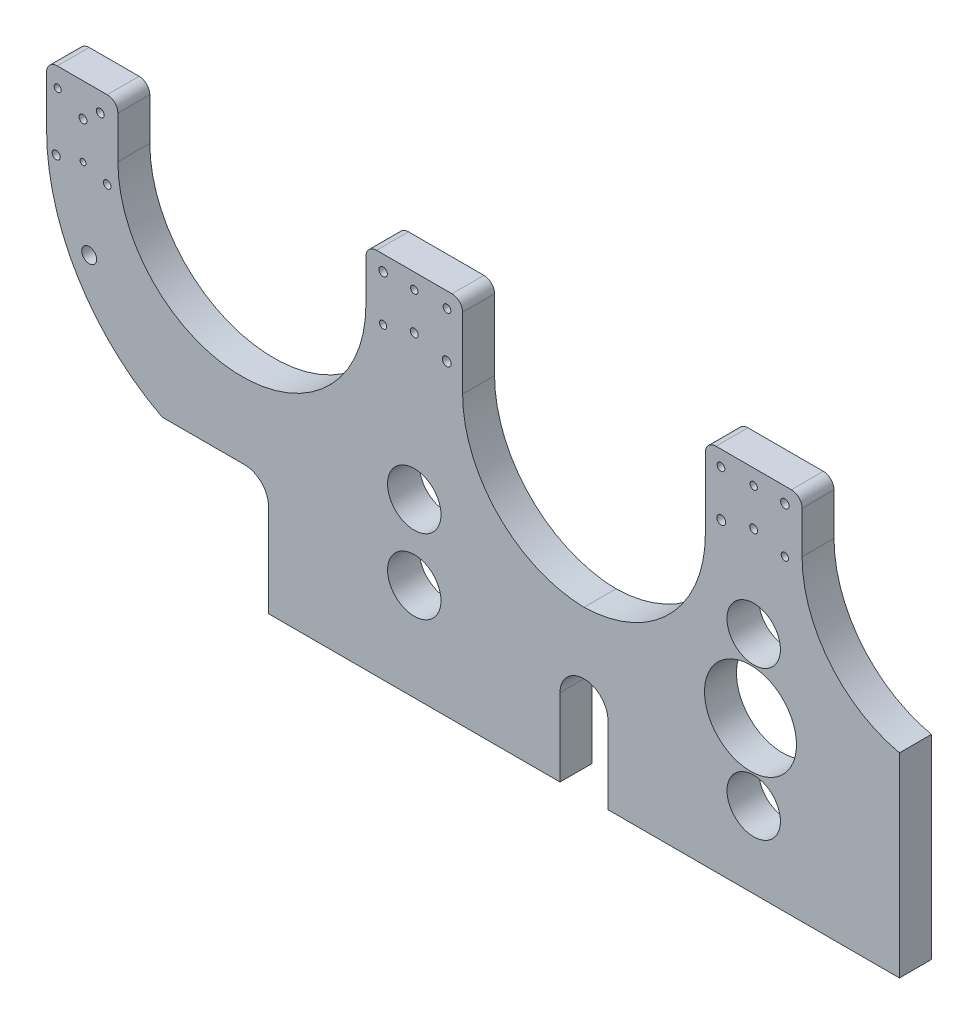
SolidWorks part; units mm, degrees
ref_plane "Front Plane" through (0, 0, 0) normal (0, 0, 1) x (1, 0, 0)
ref_plane "Top Plane" through (0, 0, 0) normal (0, 1, 0) x (1, 0, 0)
ref_plane "Right Plane" through (0, 0, 0) normal (1, 0, 0) x (0, 0, -1)
sketch "Sketch1" plane through (0, 0, 0) normal (0, 0, 1) x (1, 0, 0)
  line L0 (-439.926, 0) -> (394.926, 0) construction
  line L1 (0, 0) -> (0, 298.5319) construction
  line L2 (0, 0) -> (296.37, 0)
  line L3 (296.37, 0) -> (296.37, 183.19)
  line L4 (204.87, 336.4641) -> (204.87, 296.976)
  line L5 (194.87, 346.4641) -> (124, 346.4641)
  line L6 (114, 336.4641) -> (114, 269.898)
  line L7 (22.5, 0) -> (22.5, 72.7462)
  line L8 (-204.87, 336.4641) -> (-204.87, 296.976)
  line L9 (-194.87, 346.4641) -> (-124, 346.4641)
  line L10 (-114, 336.4641) -> (-114, 269.898)
  line L11 (0, 0) -> (-22.5, 0)
  line L12 (-22.5, 0) -> (-22.5, 72.74)
  line L13 (-22.5, 0) -> (-296.37, 0)
  line L14 (-296.37, 0) -> (-296.37, 87.5)
  line L15 (-318.87, 110) -> (-396.37, 110)
  line L16 (-321.37, 402.3721) -> (-321.37, 91.5) construction
  line L17 (-447.87, 346.4641) -> (-494.8132, 346.4641)
  line L18 (-504.8132, 336.4641) -> (-504.8132, 288.9677)
  line L19 (-437.87, 336.4641) -> (-437.87, 296.976)
  line L20 (156.4227, 184.6371) -> (156.4227, 136.4352) construction
  line L21 (156.4227, 136.4352) -> (176.8924, 185.8536) construction
  arc A0 (204.87, 296.976) -> (296.37, 183.19) centre (321.37, 296.976) ccw
  arc A1 (114, 269.898) -> (0, 153.4248) centre (-2.5, 269.898) cw
  circle A2 centre (159.44, 71.5) radius 25.1
  circle A3 centre (156.4227, 141.4349) radius 43.2021
  circle A4 centre (159.4344, 211.3701) radius 25.1
  circle A5 centre (156.4227, 141.4349) radius 32.75 construction
  circle A6 centre (156.4227, 141.4349) radius 25.1
  arc A7 (204.87, 336.4641) -> (194.87, 346.4641) centre (194.87, 336.4641) ccw
  arc A8 (124, 346.4641) -> (114, 336.4641) centre (124, 336.4641) ccw
  arc A9 (22.5, 72.7462) -> (0, 95.2462) centre (0, 72.7462) ccw
  arc A10 (-114, 269.898) -> (0, 153.4248) centre (2.5, 269.898) ccw
  arc A13 (-204.87, 296.976) -> (-437.87, 296.976) centre (-321.37, 296.976) cw
  arc A14 (-204.87, 336.4641) -> (-194.87, 346.4641) centre (-194.87, 336.4641) cw
  arc A15 (-124, 346.4641) -> (-114, 336.4641) centre (-124, 336.4641) cw
  arc A16 (-22.5, 72.74) -> (0, 95.2462) centre (0.0061, 72.74) cw
  circle A19 centre (-159.43, 91.5) radius 25.1
  circle A20 centre (-159.44, 161.5) radius 25.1
  arc A21 (-494.8132, 346.4641) -> (-504.8132, 336.4641) centre (-494.8132, 336.4641) ccw
  arc A22 (-437.87, 336.4641) -> (-447.87, 346.4641) centre (-447.87, 336.4641) ccw
  arc A23 (-504.8132, 288.9677) -> (-396.37, 110) centre (-302.9132, 288.9677) ccw
  circle A26 centre (-495.7952, 273.49) radius 3.8004
  arc A30 (-296.37, 87.5) -> (-318.87, 110) centre (-318.87, 87.5) ccw
  circle A32 centre (-464.8132, 207.5) radius 7
  circle A33 centre (-470.5815, 315.3901) radius 3.6862
  circle A35 centre (-494.4347, 328.4732) radius 3.2968
  circle A36 centre (-454.4347, 328.4732) radius 3.6939
  circle A37 centre (-447.87, 273.49) radius 3.592
  circle A38 centre (-470.5815, 280.3901) radius 2.7704
  circle A39 centre (-159.44, 331.976) radius 3.4143
  circle A40 centre (-159.44, 296.976) radius 3.7364
  circle A41 centre (-128.7089, 332.0397) radius 3.6116
  circle A42 centre (-128.958, 288.9677) radius 4.1597
  circle A43 centre (-188.7089, 288.9677) radius 3.4143
  circle A44 centre (-188.7089, 332.0397) radius 3.9834
  circle A45 centre (159.44, 296.976) radius 3.7364
  circle A46 centre (159.44, 331.976) radius 3.4143
  circle A47 centre (128.7089, 332.0397) radius 3.6116
  circle A48 centre (128.958, 288.9677) radius 4.1597
  circle A49 centre (188.7089, 288.9677) radius 3.4143
  circle A50 centre (188.7089, 332.0397) radius 3.9834
  circle A51 centre (156.4227, 174.1849) radius 4.25
  circle A53 centre (170.7018, 170.9081) radius 4.25
  point P26 (204.87, 346.4641)
  point P29 (114, 346.4641)
  point P80 (-296.37, 110)
  dimension "D2" = 116.5
  dimension "D5" = 116.5
  dimension "D12" = 50.2
  dimension "D13" = 50.2
  dimension "D14" = 86.4043
  dimension "D15" = 65.5
  dimension "D16" = 50.2
  dimension "D17" = 10
  dimension "D18" = 10
  dimension "D19" = 22.5
  dimension "D24" = 50.2
  dimension "D25" = 136.94
  dimension "D27" = 116.5
  dimension "D29" = 10
  dimension "D28" = 201.9
  dimension "D34" = 22.5
  dimension "D35" = 14
  dimension "D31" = 40
  dimension "D39" = 60
  dimension "D41" = 8.5
  dimension "D42" = 8.5
  dimension "D1" = 183.19
  dimension "D3" = 90.87
  dimension "D4" = 91.5
  dimension "D6" = 136.94
  dimension "D7" = 22.5
  dimension "D8" = 273.87
  dimension "D9" = 70
  dimension "D10" = 70
  dimension "D11" = 71.5
  dimension "D20" = 22.5
  dimension "D21" = 273.87
  dimension "D22" = 91.5
  dimension "D23" = 161.5
  dimension "D26" = 110
  dimension "D30" = 100
  dimension "D32" = 35
  dimension "D33" = 55
  dimension "D36" = 40
  dimension "D37" = 97.5
  dimension "D38" = 65.99
  dimension "D40" = 35
extrude "Boss-Extrude1" add sketch "Sketch1" along normal blind 30 contours A30 L14 L13 L12 A16 A9 L7 L2 L3 A0 L4 A7 L5 A8 L6 A1 A10 L10 A15 L9 A14 L8 A13 L19 A22 L17 A21 L18 A23 L15 A49 A47 A45 A44 A43 A42 A41 A40 A39 A38
